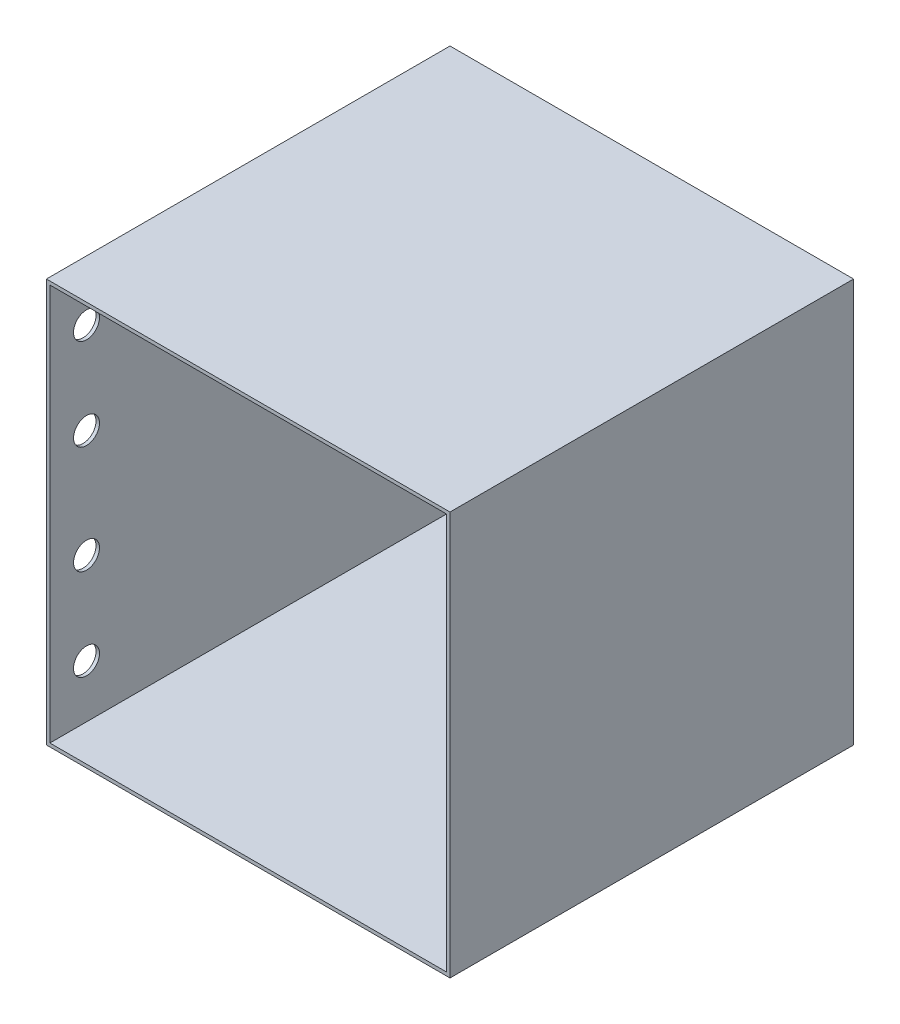
SolidWorks part; units mm, degrees
material "AISI 304"
ref_plane "Alzado" through (0, 0, 0) normal (0, 0, 1) x (1, 0, 0)
ref_plane "Planta" through (0, 0, 0) normal (0, 1, 0) x (1, 0, 0)
ref_plane "Vista lateral" through (0, 0, 0) normal (1, 0, 0) x (0, 0, -1)
sketch "Croquis1" plane through (0, 0, 0) normal (0, 0, 1) x (1, 0, 0)
  line L1 (0, 0) -> (70, 0)
  line L2 (0, 0) -> (0, 70)
  line L3 (0, 70) -> (70, 70)
  line L4 (70, 0) -> (70, 70)
  dimension "D1" = 70
  dimension "D2" = 70
extrude "Saliente-Extruir1" add sketch "Croquis1" along normal blind 70
shell "Vaciado1" thickness 0.6
hole_wizard "Taladro de margen para M41" positions "Croquis2" profile "Croquis3" hole size "M4" standard "Ansi Metric"
sketch "Croquis2" plane through (-1, -81.2, 39.7304) normal (-1, 0, 0) x (0, 1, 0)
  point P0 (90.9625, -23.9196)
  point P3 (106.8375, -23.9196)
  point P6 (125.5625, -23.9196)
  point P9 (141.4375, -23.9196)
sketch "Croquis3" plane through (-1, 9.7625, 63.65) normal (0, 1, 0) x (0, 0, 1)
  line L0 (0, 0) -> (0, 1.599)
  line L1 (0, 1.599) -> (2.25, 1.599)
  line L2 (2.25, 1.599) -> (2.25, 0)
  line L3 (2.25, 0) -> (0, 0)
  line L4 (0, -6.35) -> (0, 107.95) construction
  dimension "Diámetro de taladro hasta el siguiente" = 4.5
  dimension "Profundidad de taladro hasta el siguiente" = 1.599
